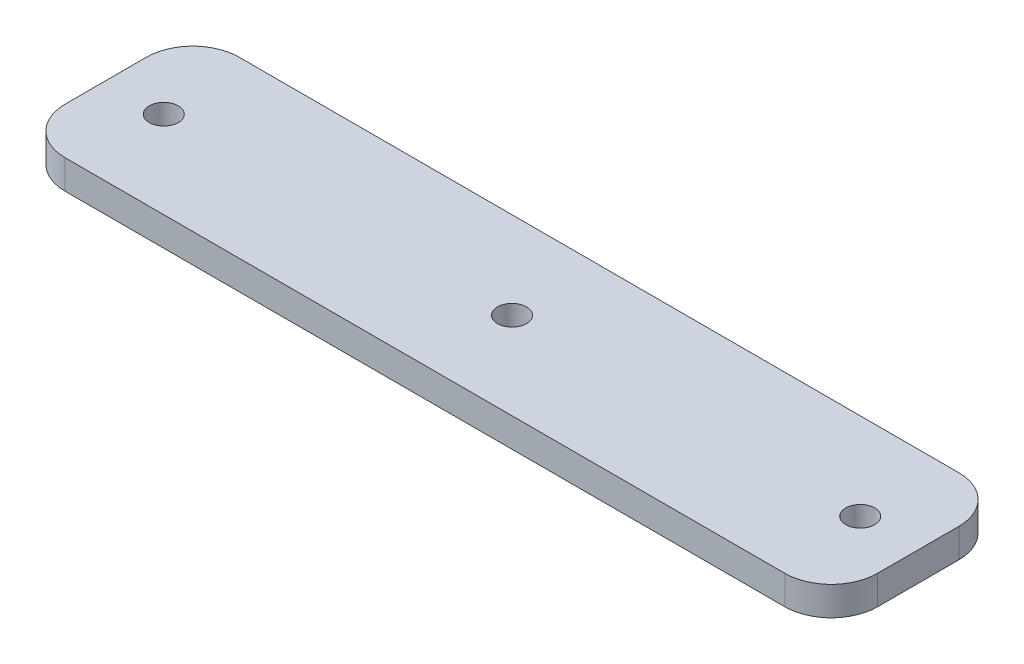
SolidWorks part; units mm, degrees
ref_plane "Front Plane" through (0, 0, 0) normal (0, 0, 1) x (1, 0, 0)
ref_plane "Top Plane" through (0, 0, 0) normal (0, 1, 0) x (1, 0, 0)
ref_plane "Right Plane" through (0, 0, 0) normal (1, 0, 0) x (0, 0, -1)
sketch "Sketch1" plane through (0, 0, 0) normal (0, 1, 0) x (1, 0, 0)
  line L1 (10.16, 0) -> (167.64, 0)
  line L2 (0, -10.16) -> (0, -27.94)
  line L3 (10.16, -38.1) -> (167.64, -38.1)
  line L4 (177.8, -10.16) -> (177.8, -27.94)
  circle A0 centre (12.7, -19.05) radius 3.175
  circle A1 centre (88.9, -19.05) radius 3.175
  circle A2 centre (165.1, -19.05) radius 3.175
  arc A3 (177.8, -10.16) -> (167.64, 0) centre (167.64, -10.16) ccw
  arc A4 (177.8, -27.94) -> (167.64, -38.1) centre (167.64, -27.94) cw
  arc A5 (0, -27.94) -> (10.16, -38.1) centre (10.16, -27.94) ccw
  arc A6 (0, -10.16) -> (10.16, 0) centre (10.16, -10.16) cw
  point P19 (0, 0)
  dimension "D1" = 10.16
extrude "Boss-Extrude1" add sketch "Sketch1" along normal blind 6.35
